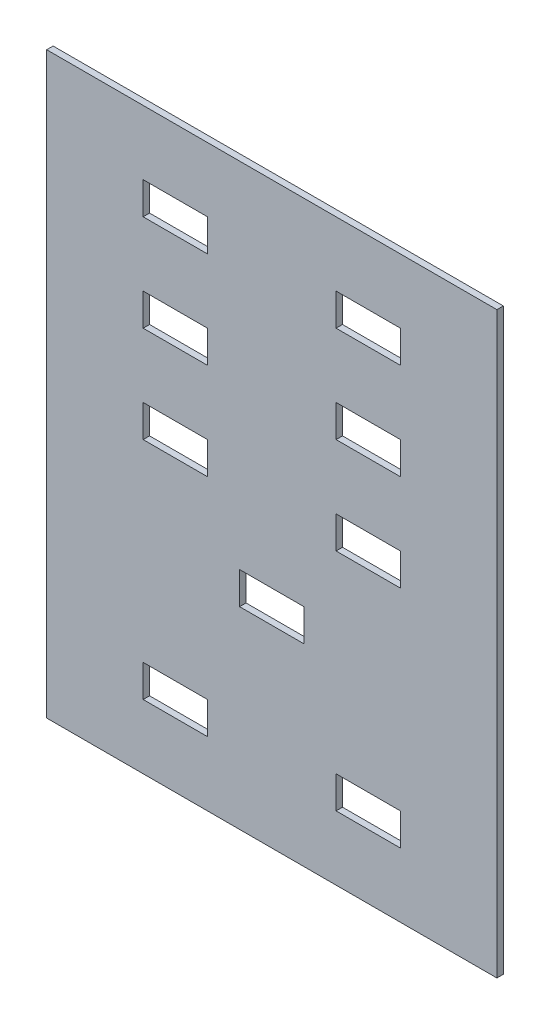
SolidWorks part; units mm, degrees
material "Brass"
ref_plane "Front Plane" through (0, 0, 0) normal (0, 0, 1) x (1, 0, 0)
ref_plane "Top Plane" through (0, 0, 0) normal (0, 1, 0) x (1, 0, 0)
ref_plane "Right Plane" through (0, 0, 0) normal (1, 0, 0) x (0, 0, -1)
sketch "Sketch1" plane through (0, 0, 0) normal (0, 0, 1) x (1, 0, 0)
  line L1 (0, 0) -> (350, 0)
  line L2 (0, 0) -> (0, 450)
  line L3 (0, 450) -> (350, 450)
  line L4 (350, 0) -> (350, 450)
  dimension "D1" = 350
  dimension "D2" = 450
extrude "Boss-Extrude1" add sketch "Sketch1" along normal blind 5
sketch "Sketch2" plane through (0, 0, 5) normal (0, 0, 1) x (1, 0, 0)
  line L2 (75, 375) -> (125, 375)
  line L3 (75, 375) -> (75, 400)
  line L4 (75, 400) -> (125, 400)
  line L5 (350, 450) -> (0, 450) construction
  line L6 (175, 450) -> (175, 207.535) construction
  line L7 (125, 375) -> (125, 400)
  line L8 (75, 375) -> (125, 400) construction
  line L9 (75, 400) -> (125, 375) construction
  point P0 (100, 387.5)
  dimension "D1" = 150
  dimension "D2" = 50
  dimension "D3" = 25
  dimension "D4" = 50
extrude "Cut-Extrude1" cut sketch "Sketch2" against normal through all
sketch "Sketch3" plane through (0, 0, 5) normal (0, 0, 1) x (1, 0, 0)
  line L0 (125, 387.5) -> (362.4149, 387.5) construction
  line L2 (125, 375) -> (125, 400) construction
  line L3 (100, 375) -> (100, 353.9352) construction
  line L4 (75, 375) -> (125, 375) construction
  point P8 (250, 387.5)
  point P9 (250, 312.5)
  point P10 (100, 312.5)
  point P11 (100, 237.5)
  point P13 (250, 237.5)
  point P14 (175, 162.5)
  point P15 (100, 62.5)
  point P16 (250, 62.5)
  dimension "D1" = 75
  dimension "D2" = 150
  dimension "D3" = 75
  dimension "D4" = 150
  dimension "D5" = 225
  dimension "D6" = 325
pattern_sketch "Sketch-Pattern1" of "Cut-Extrude1" driven by "Sketch3"
